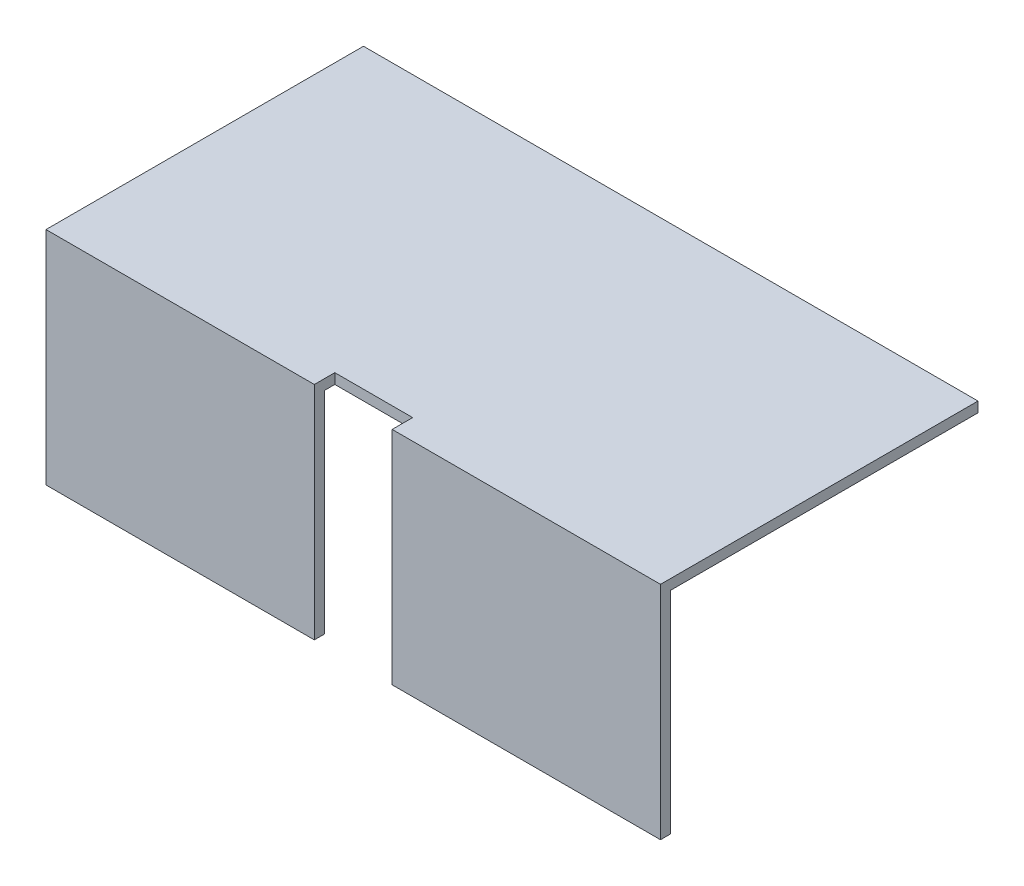
SolidWorks part; units mm, degrees
ref_plane "Front Plane" through (0, 0, 0) normal (0, 0, 1) x (1, 0, 0)
ref_plane "Top Plane" through (0, 0, 0) normal (0, 1, 0) x (1, 0, 0)
ref_plane "Right Plane" through (0, 0, 0) normal (1, 0, 0) x (0, 0, -1)
sketch "Sketch1" plane through (0, 0, 0) normal (1, 0, 0) x (0, 0, -1)
  line L0 (0, 0) -> (-150, 0)
  line L1 (-150, 0) -> (-150, -103)
  dimension "D1" = 150
  dimension "D2" = 103
extrude "Extrude-Thin1" add sketch "Sketch1" along normal blind 300 thin
sketch "Sketch2" plane through (0, 5, 0) normal (0, 1, 0) x (1, 0, 0)
  line L0 (300, -155) -> (0, -155) construction
  line L1 (131, -145) -> (169, -145)
  line L2 (131, -145) -> (131, -155)
  line L3 (131, -155) -> (169, -155)
  line L4 (169, -145) -> (169, -155)
  line L5 (0, 0) -> (0, -155) construction
  dimension "D1" = 38
  dimension "D2" = 131
  dimension "D3" = 10
extrude "Cut-Extrude1" cut sketch "Sketch2" against normal blind 130
